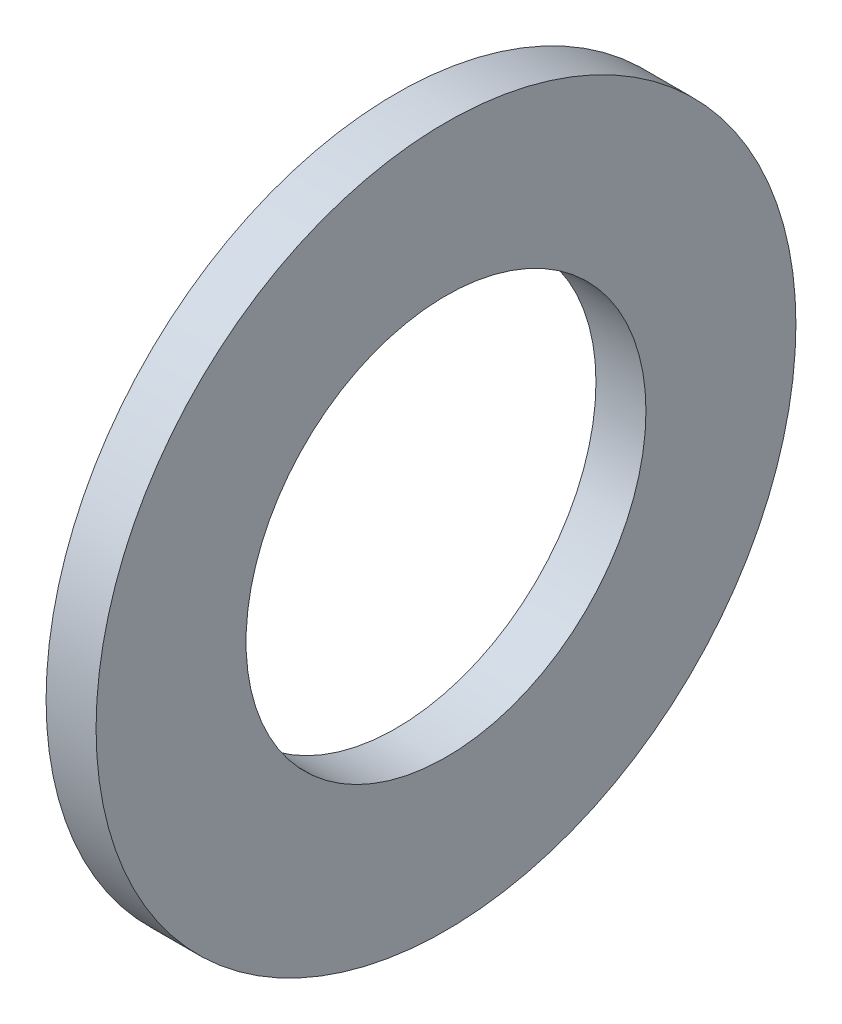
SolidWorks part; units mm, degrees
ref_plane "前视基准面" through (0, 0, 0) normal (0, 0, 1) x (1, 0, 0)
ref_plane "上视基准面" through (0, 0, 0) normal (0, 1, 0) x (1, 0, 0)
ref_plane "右视基准面" through (0, 0, 0) normal (1, 0, 0) x (0, 0, -1)
other "Configuration Table"
sketch "草图1" plane through (0, 0, 0) normal (1, 0, 0) x (0, 0, -1)
  circle A0 centre (0, 0) radius 2
  circle A1 centre (0, 0) radius 3.5
  dimension "D1" = 4
  dimension "D2" = 7
extrude "凸台-拉伸1" add sketch "草图1" along normal blind 0.5 contours A0 | A1
